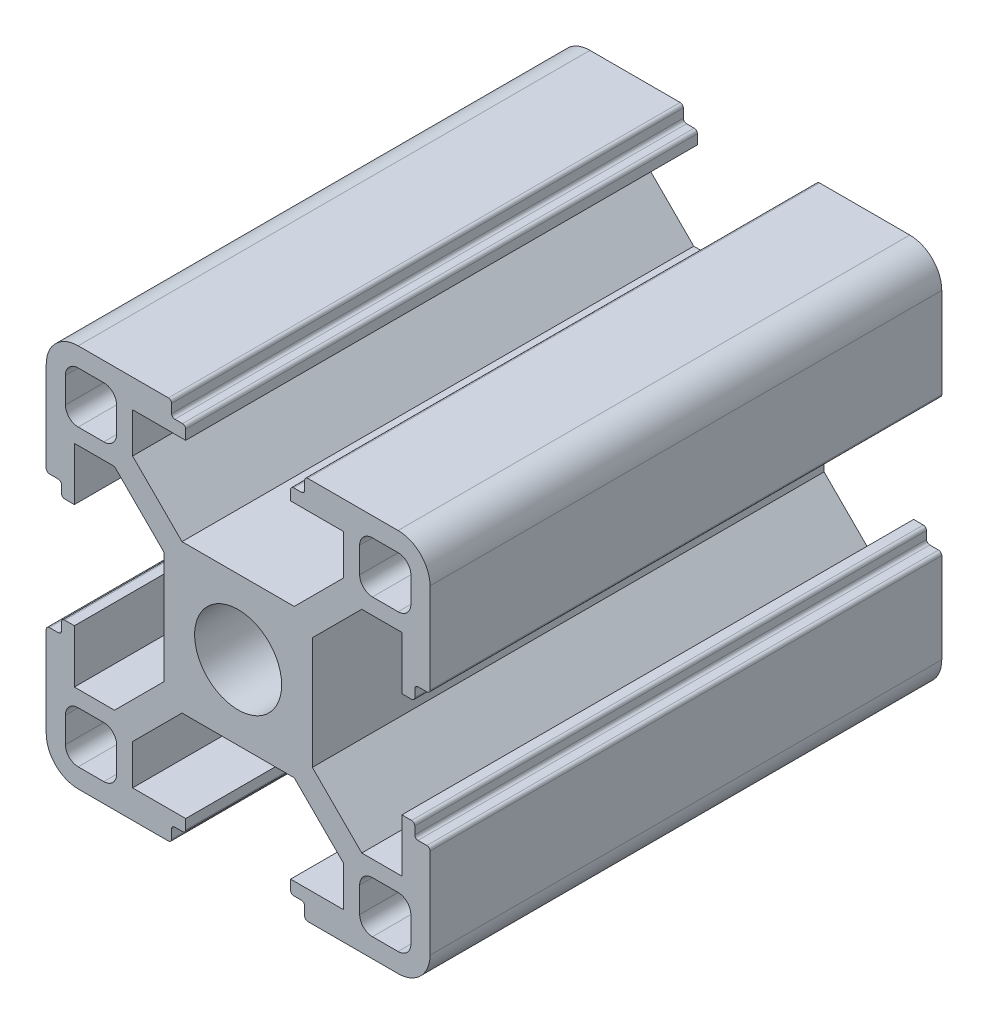
SolidWorks part; units mm, degrees
ref_plane "Front Plane" through (0, 0, 0) normal (0, 0, 1) x (1, 0, 0)
ref_plane "Top Plane" through (0, 0, 0) normal (0, 1, 0) x (1, 0, 0)
ref_plane "Right Plane" through (0, 0, 0) normal (1, 0, 0) x (0, 0, -1)
sketch "Sketch1" plane through (0, 0, 0) normal (0, 0, 1) x (1, 0, 0)
  line L0 (0, -5.8) -> (0, 5.8) construction
  line L1 (0, 0) -> (-15, 15) construction
  line L2 (-15, 15) -> (-5.2, 15)
  line L3 (-5.2, 15) -> (-5.2, 13.8083)
  line L4 (-5.2, 13.8083) -> (-4.1, 13.8083)
  line L5 (-4.1, 13.8083) -> (-4.1, 12.8)
  line L6 (-4.1, 12.8) -> (-8.25, 12.8)
  line L7 (-8.25, 12.8) -> (-8.25, 9.6642)
  line L8 (-8.25, 9.6642) -> (-4.3858, 5.8)
  line L9 (-4.3858, 5.8) -> (4.3858, 5.8)
  line L10 (-5.8, 4.3858) -> (-5.8, -4.3858)
  line L11 (-9.6642, 8.25) -> (-5.8, 4.3858)
  line L12 (-12.8, 8.25) -> (-9.6642, 8.25)
  line L13 (-12.8, 4.1) -> (-12.8, 8.25)
  line L14 (-13.8083, 4.1) -> (-12.8, 4.1)
  line L15 (-13.8083, 5.2) -> (-13.8083, 4.1)
  line L16 (-15, 5.2) -> (-13.8083, 5.2)
  line L17 (-15, 15) -> (-15, 5.2)
  line L18 (0, 0) -> (15, 15) construction
  line L19 (15, 15) -> (15, 5.2)
  line L20 (15, 5.2) -> (13.8083, 5.2)
  line L21 (13.8083, 5.2) -> (13.8083, 4.1)
  line L22 (13.8083, 4.1) -> (12.8, 4.1)
  line L23 (12.8, 4.1) -> (12.8, 8.25)
  line L24 (12.8, 8.25) -> (9.6642, 8.25)
  line L25 (9.6642, 8.25) -> (5.8, 4.3858)
  line L26 (5.8, 4.3858) -> (5.8, -4.3858)
  line L27 (8.25, 9.6642) -> (4.3858, 5.8)
  line L28 (8.25, 12.8) -> (8.25, 9.6642)
  line L29 (4.1, 12.8) -> (8.25, 12.8)
  line L30 (4.1, 13.8083) -> (4.1, 12.8)
  line L31 (5.2, 13.8083) -> (4.1, 13.8083)
  line L32 (5.2, 15) -> (5.2, 13.8083)
  line L33 (15, 15) -> (5.2, 15)
  line L34 (0, 0) -> (3.5826, 0) construction
  line L35 (0, 0) -> (15, -15) construction
  line L36 (0, 0) -> (-15, -15) construction
  line L37 (15, -15) -> (5.2, -15)
  line L38 (5.2, -15) -> (5.2, -13.8083)
  line L39 (5.2, -13.8083) -> (4.1, -13.8083)
  line L40 (4.1, -13.8083) -> (4.1, -12.8)
  line L41 (4.1, -12.8) -> (8.25, -12.8)
  line L42 (8.25, -12.8) -> (8.25, -9.6642)
  line L43 (8.25, -9.6642) -> (4.3858, -5.8)
  line L44 (9.6642, -8.25) -> (5.8, -4.3858)
  line L45 (12.8, -8.25) -> (9.6642, -8.25)
  line L46 (12.8, -4.1) -> (12.8, -8.25)
  line L47 (13.8083, -4.1) -> (12.8, -4.1)
  line L48 (13.8083, -5.2) -> (13.8083, -4.1)
  line L49 (15, -5.2) -> (13.8083, -5.2)
  line L50 (15, -15) -> (15, -5.2)
  line L51 (-15, -15) -> (-15, -5.2)
  line L52 (-15, -5.2) -> (-13.8083, -5.2)
  line L53 (-13.8083, -5.2) -> (-13.8083, -4.1)
  line L54 (-13.8083, -4.1) -> (-12.8, -4.1)
  line L55 (-12.8, -4.1) -> (-12.8, -8.25)
  line L56 (-12.8, -8.25) -> (-9.6642, -8.25)
  line L57 (-9.6642, -8.25) -> (-5.8, -4.3858)
  line L58 (-4.3858, -5.8) -> (4.3858, -5.8)
  line L59 (-8.25, -9.6642) -> (-4.3858, -5.8)
  line L60 (-8.25, -12.8) -> (-8.25, -9.6642)
  line L61 (-4.1, -12.8) -> (-8.25, -12.8)
  line L62 (-4.1, -13.8083) -> (-4.1, -12.8)
  line L63 (-5.2, -13.8083) -> (-4.1, -13.8083)
  line L64 (-5.2, -15) -> (-5.2, -13.8083)
  line L65 (-15, -15) -> (-5.2, -15)
  point P30 (0, 5.8)
  point P48 (5.8, 0)
  point P61 (-5.8, 0)
  dimension "D2" = 15
  dimension "D3" = 1
  dimension "D4" = 4.1
  dimension "D5" = 5.2
  dimension "D6" = 2.2
  dimension "D7" = 8.25
  dimension "D8" = 9.2
extrude "Boss-Extrude1" add sketch "Sketch1" along normal blind 250
sketch "Sketch2" plane through (0, 0, 250) normal (0, 0, 1) x (1, 0, 0)
  line L0 (0, 0) -> (0, 17.0054) construction
  line L1 (0, 0) -> (20.7717, 0) construction
  line L2 (-5.2, 15) -> (-15, 15) construction
  line L3 (-12.5, 13.5) -> (-10.5, 13.5)
  line L4 (-13.5, 12.5) -> (-13.5, 10.5)
  line L5 (-12.5, 9.5) -> (-10.5, 9.5)
  line L6 (-9.5, 12.5) -> (-9.5, 10.5)
  line L7 (-13.5, 13.5) -> (-9.5, 9.5) construction
  line L8 (-13.5, 9.5) -> (-9.5, 13.5) construction
  line L9 (-15, 15) -> (-15, 5.2) construction
  line L10 (13.5, 9.5) -> (9.5, 13.5) construction
  line L11 (13.5, 13.5) -> (9.5, 9.5) construction
  line L12 (9.5, 12.5) -> (9.5, 10.5)
  line L13 (12.5, 9.5) -> (10.5, 9.5)
  line L14 (13.5, 12.5) -> (13.5, 10.5)
  line L15 (12.5, 13.5) -> (10.5, 13.5)
  line L16 (13.5, -13.5) -> (9.5, -9.5) construction
  line L17 (13.5, -9.5) -> (9.5, -13.5) construction
  line L18 (-13.5, -9.5) -> (-9.5, -13.5) construction
  line L19 (-13.5, -13.5) -> (-9.5, -9.5) construction
  line L20 (12.5, -13.5) -> (10.5, -13.5)
  line L21 (13.5, -12.5) -> (13.5, -10.5)
  line L22 (12.5, -9.5) -> (10.5, -9.5)
  line L23 (9.5, -12.5) -> (9.5, -10.5)
  line L24 (-9.5, -12.5) -> (-9.5, -10.5)
  line L25 (-12.5, -9.5) -> (-10.5, -9.5)
  line L26 (-13.5, -12.5) -> (-13.5, -10.5)
  line L27 (-12.5, -13.5) -> (-10.5, -13.5)
  arc A0 (-12.5, 13.5) -> (-13.5, 12.5) centre (-12.5, 12.5) ccw
  arc A1 (-13.5, 10.5) -> (-12.5, 9.5) centre (-12.5, 10.5) ccw
  arc A2 (-10.5, 9.5) -> (-9.5, 10.5) centre (-10.5, 10.5) ccw
  arc A3 (-10.5, 13.5) -> (-9.5, 12.5) centre (-10.5, 12.5) cw
  arc A4 (10.5, 13.5) -> (9.5, 12.5) centre (10.5, 12.5) ccw
  arc A5 (10.5, 9.5) -> (9.5, 10.5) centre (10.5, 10.5) cw
  arc A6 (13.5, 10.5) -> (12.5, 9.5) centre (12.5, 10.5) cw
  arc A7 (12.5, 13.5) -> (13.5, 12.5) centre (12.5, 12.5) cw
  arc A8 (12.5, -13.5) -> (13.5, -12.5) centre (12.5, -12.5) ccw
  arc A9 (13.5, -10.5) -> (12.5, -9.5) centre (12.5, -10.5) ccw
  arc A10 (10.5, -9.5) -> (9.5, -10.5) centre (10.5, -10.5) ccw
  arc A11 (10.5, -13.5) -> (9.5, -12.5) centre (10.5, -12.5) cw
  arc A12 (-10.5, -13.5) -> (-9.5, -12.5) centre (-10.5, -12.5) ccw
  arc A13 (-10.5, -9.5) -> (-9.5, -10.5) centre (-10.5, -10.5) cw
  arc A14 (-13.5, -10.5) -> (-12.5, -9.5) centre (-12.5, -10.5) cw
  arc A15 (-12.5, -13.5) -> (-13.5, -12.5) centre (-12.5, -12.5) cw
  circle A16 centre (0, 0) radius 3.4
  point P3 (-11.5, 11.5)
  point P41 (11.5, 11.5)
  point P74 (11.5, -11.5)
  point P75 (-11.5, -11.5)
  dimension "D5" = 1
  dimension "D6" = 6.8
  dimension "D1" = 1.5
  dimension "D2" = 1.5
  dimension "D3" = 4
  dimension "D4" = 4
extrude "Cut-Extrude1" cut sketch "Sketch2" against normal through all
fillet "Fillet1" radius 2.5 4 edges at (-15, -15, 125) (15, -15, 125) (15, 15, 125) (-15, 15, 125)
fillet "Fillet2" radius 0.25 24 edges at (-13.8083, 5.2, 125) (-13.8083, 4.1, 125) (-15, 5.2, 125) (-13.8083, -4.1, 125) (-13.8083, -5.2, 125) (-15, -5.2, 125) (-5.2, -15, 125) (-5.2, -13.8083, 125) (-4.1, -13.8083, 125) (4.1, -13.8083, 125) (5.2, -13.8083, 125) (5.2, -15, 125) (13.8083, -5.2, 125) (13.8083, -4.1, 125) (15, -5.2, 125) (13.8083, 4.1, 125) (13.8083, 5.2, 125) (15, 5.2, 125) (-4.1, 13.8083, 125) (-5.2, 13.8083, 125) (4.1, 13.8083, 125) (5.2, 13.8083, 125) (5.2, 15, 125) (-5.2, 15, 125)
sketch "Sketch3" plane through (0, 0, 0) normal (0, 0, -1) x (-1, 0, 0)
  line L0 (-12.5, 13.5) -> (-10.5, 13.5) construction
  line L1 (-10.5, 9.5) -> (-12.5, 9.5) construction
  line L2 (-9.5, 12.5) -> (-9.5, 10.5) construction
  line L3 (-13.5, 10.5) -> (-13.5, 12.5) construction
  line L4 (-9.5, 12.5) -> (-9.5, 10.5)
  line L5 (-12.5, 13.5) -> (-10.5, 13.5)
  line L6 (-13.5, 10.5) -> (-13.5, 12.5)
  line L7 (-10.5, 9.5) -> (-12.5, 9.5)
  line L8 (10.5, 13.5) -> (12.5, 13.5) construction
  line L9 (9.5, 10.5) -> (9.5, 12.5) construction
  line L10 (13.5, 12.5) -> (13.5, 10.5) construction
  line L11 (12.5, 9.5) -> (10.5, 9.5) construction
  line L12 (12.5, 9.5) -> (10.5, 9.5)
  line L13 (13.5, 12.5) -> (13.5, 10.5)
  line L14 (9.5, 10.5) -> (9.5, 12.5)
  line L15 (10.5, 13.5) -> (12.5, 13.5)
  line L16 (9.5, -12.5) -> (9.5, -10.5) construction
  line L17 (12.5, -13.5) -> (10.5, -13.5) construction
  line L18 (13.5, -10.5) -> (13.5, -12.5) construction
  line L19 (10.5, -9.5) -> (12.5, -9.5) construction
  line L20 (9.5, -12.5) -> (9.5, -10.5)
  line L21 (12.5, -13.5) -> (10.5, -13.5)
  line L22 (13.5, -10.5) -> (13.5, -12.5)
  line L23 (10.5, -9.5) -> (12.5, -9.5)
  line L24 (-9.5, -10.5) -> (-9.5, -12.5) construction
  line L25 (-10.5, -13.5) -> (-12.5, -13.5) construction
  line L26 (-13.5, -12.5) -> (-13.5, -10.5) construction
  line L27 (-12.5, -9.5) -> (-10.5, -9.5) construction
  line L28 (-9.5, -10.5) -> (-9.5, -12.5)
  line L29 (-10.5, -13.5) -> (-12.5, -13.5)
  line L30 (-13.5, -12.5) -> (-13.5, -10.5)
  line L31 (-12.5, -9.5) -> (-10.5, -9.5)
  line L60 (12.8, 4.1) -> (13.5583, 4.1)
  line L61 (13.8083, 4.35) -> (13.8083, 4.95)
  line L62 (14.0583, 5.2) -> (14.75, 5.2)
  line L63 (15, 5.45) -> (15, 12.5)
  line L64 (12.5, 15) -> (5.45, 15)
  line L65 (5.2, 14.75) -> (5.2, 14.0583)
  line L66 (4.95, 13.8083) -> (4.35, 13.8083)
  line L67 (4.1, 13.5583) -> (4.1, 12.8)
  line L68 (4.1, 12.8) -> (8.25, 12.8)
  line L69 (8.25, 12.8) -> (8.25, 9.6642)
  line L70 (8.25, 9.6642) -> (4.3858, 5.8)
  line L71 (4.3858, 5.8) -> (-4.3858, 5.8)
  line L72 (-4.3858, 5.8) -> (-8.25, 9.6642)
  line L73 (-8.25, 9.6642) -> (-8.25, 12.8)
  line L74 (-8.25, 12.8) -> (-4.1, 12.8)
  line L75 (-4.1, 12.8) -> (-4.1, 13.5583)
  line L76 (-4.35, 13.8083) -> (-4.95, 13.8083)
  line L77 (-5.2, 14.0583) -> (-5.2, 14.75)
  line L78 (-5.45, 15) -> (-12.5, 15)
  line L79 (-15, 12.5) -> (-15, 5.45)
  line L80 (-14.75, 5.2) -> (-14.0583, 5.2)
  line L81 (-13.8083, 4.95) -> (-13.8083, 4.35)
  line L82 (-13.5583, 4.1) -> (-12.8, 4.1)
  line L83 (-12.8, 4.1) -> (-12.8, 8.25)
  line L84 (-12.8, 8.25) -> (-9.6642, 8.25)
  line L85 (-9.6642, 8.25) -> (-5.8, 4.3858)
  line L86 (-5.8, 4.3858) -> (-5.8, -4.3858)
  line L87 (-5.8, -4.3858) -> (-9.6642, -8.25)
  line L88 (-9.6642, -8.25) -> (-12.8, -8.25)
  line L89 (-12.8, -8.25) -> (-12.8, -4.1)
  line L90 (-12.8, -4.1) -> (-13.5583, -4.1)
  line L91 (-13.8083, -4.35) -> (-13.8083, -4.95)
  line L92 (-14.0583, -5.2) -> (-14.75, -5.2)
  line L93 (-15, -5.45) -> (-15, -12.5)
  line L94 (-12.5, -15) -> (-5.45, -15)
  line L95 (-5.2, -14.75) -> (-5.2, -14.0583)
  line L96 (-4.95, -13.8083) -> (-4.35, -13.8083)
  line L97 (-4.1, -13.5583) -> (-4.1, -12.8)
  line L98 (-4.1, -12.8) -> (-8.25, -12.8)
  line L99 (-8.25, -12.8) -> (-8.25, -9.6642)
  line L100 (-8.25, -9.6642) -> (-4.3858, -5.8)
  line L101 (-4.3858, -5.8) -> (4.3858, -5.8)
  line L102 (4.3858, -5.8) -> (8.25, -9.6642)
  line L103 (8.25, -9.6642) -> (8.25, -12.8)
  line L104 (8.25, -12.8) -> (4.1, -12.8)
  line L105 (4.1, -12.8) -> (4.1, -13.5583)
  line L106 (4.35, -13.8083) -> (4.95, -13.8083)
  line L107 (5.2, -14.0583) -> (5.2, -14.75)
  line L108 (5.45, -15) -> (12.5, -15)
  line L109 (15, -12.5) -> (15, -5.45)
  line L110 (14.75, -5.2) -> (14.0583, -5.2)
  line L111 (13.8083, -4.95) -> (13.8083, -4.35)
  line L112 (13.5583, -4.1) -> (12.8, -4.1)
  line L113 (12.8, -4.1) -> (12.8, -8.25)
  line L114 (12.8, -8.25) -> (9.6642, -8.25)
  line L115 (9.6642, -8.25) -> (5.8, -4.3858)
  line L116 (5.8, -4.3858) -> (5.8, 4.3858)
  line L117 (5.8, 4.3858) -> (9.6642, 8.25)
  line L118 (9.6642, 8.25) -> (12.8, 8.25)
  line L119 (12.8, 8.25) -> (12.8, 4.1)
  line L120 (12.8, 4.1) -> (13.5583, 4.1)
  line L121 (13.8083, 4.35) -> (13.8083, 4.95)
  line L122 (14.0583, 5.2) -> (14.75, 5.2)
  line L123 (15, 5.45) -> (15, 12.5)
  line L124 (12.5, 15) -> (5.45, 15)
  line L125 (5.2, 14.75) -> (5.2, 14.0583)
  line L126 (4.95, 13.8083) -> (4.35, 13.8083)
  line L127 (4.1, 13.5583) -> (4.1, 12.8)
  line L128 (4.1, 12.8) -> (8.25, 12.8)
  line L129 (8.25, 12.8) -> (8.25, 9.6642)
  line L130 (8.25, 9.6642) -> (4.3858, 5.8)
  line L131 (4.3858, 5.8) -> (-4.3858, 5.8)
  line L132 (-4.3858, 5.8) -> (-8.25, 9.6642)
  line L133 (-8.25, 9.6642) -> (-8.25, 12.8)
  line L134 (-8.25, 12.8) -> (-4.1, 12.8)
  line L135 (-4.1, 12.8) -> (-4.1, 13.5583)
  line L136 (-4.35, 13.8083) -> (-4.95, 13.8083)
  line L137 (-5.2, 14.0583) -> (-5.2, 14.75)
  line L138 (-5.45, 15) -> (-12.5, 15)
  line L139 (-15, 12.5) -> (-15, 5.45)
  line L140 (-14.75, 5.2) -> (-14.0583, 5.2)
  line L141 (-13.8083, 4.95) -> (-13.8083, 4.35)
  line L142 (-13.5583, 4.1) -> (-12.8, 4.1)
  line L143 (-12.8, 4.1) -> (-12.8, 8.25)
  line L144 (-12.8, 8.25) -> (-9.6642, 8.25)
  line L145 (-9.6642, 8.25) -> (-5.8, 4.3858)
  line L146 (-5.8, 4.3858) -> (-5.8, -4.3858)
  line L147 (-5.8, -4.3858) -> (-9.6642, -8.25)
  line L148 (-9.6642, -8.25) -> (-12.8, -8.25)
  line L149 (-12.8, -8.25) -> (-12.8, -4.1)
  line L150 (-12.8, -4.1) -> (-13.5583, -4.1)
  line L151 (-13.8083, -4.35) -> (-13.8083, -4.95)
  line L152 (-14.0583, -5.2) -> (-14.75, -5.2)
  line L153 (-15, -5.45) -> (-15, -12.5)
  line L154 (-12.5, -15) -> (-5.45, -15)
  line L155 (-5.2, -14.75) -> (-5.2, -14.0583)
  line L156 (-4.95, -13.8083) -> (-4.35, -13.8083)
  line L157 (-4.1, -13.5583) -> (-4.1, -12.8)
  line L158 (-4.1, -12.8) -> (-8.25, -12.8)
  line L159 (-8.25, -12.8) -> (-8.25, -9.6642)
  line L160 (-8.25, -9.6642) -> (-4.3858, -5.8)
  line L161 (-4.3858, -5.8) -> (4.3858, -5.8)
  line L162 (4.3858, -5.8) -> (8.25, -9.6642)
  line L163 (8.25, -9.6642) -> (8.25, -12.8)
  line L164 (8.25, -12.8) -> (4.1, -12.8)
  line L165 (4.1, -12.8) -> (4.1, -13.5583)
  line L166 (4.35, -13.8083) -> (4.95, -13.8083)
  line L167 (5.2, -14.0583) -> (5.2, -14.75)
  line L168 (5.45, -15) -> (12.5, -15)
  line L169 (15, -12.5) -> (15, -5.45)
  line L170 (14.75, -5.2) -> (14.0583, -5.2)
  line L171 (13.8083, -4.95) -> (13.8083, -4.35)
  line L172 (13.5583, -4.1) -> (12.8, -4.1)
  line L173 (12.8, -4.1) -> (12.8, -8.25)
  line L174 (12.8, -8.25) -> (9.6642, -8.25)
  line L175 (9.6642, -8.25) -> (5.8, -4.3858)
  line L176 (5.8, -4.3858) -> (5.8, 4.3858)
  line L177 (5.8, 4.3858) -> (9.6642, 8.25)
  line L178 (9.6642, 8.25) -> (12.8, 8.25)
  line L179 (12.8, 8.25) -> (12.8, 4.1)
  circle A0 centre (0, 0) radius 3.4 construction
  circle A1 centre (0, 0) radius 3.4
  arc A2 (-12.5, 13.5) -> (-13.5, 12.5) centre (-12.5, 12.5) ccw construction
  arc A3 (-9.5, 12.5) -> (-10.5, 13.5) centre (-10.5, 12.5) ccw construction
  arc A4 (-13.5, 10.5) -> (-12.5, 9.5) centre (-12.5, 10.5) ccw construction
  arc A5 (-10.5, 9.5) -> (-9.5, 10.5) centre (-10.5, 10.5) ccw construction
  arc A6 (-9.5, 12.5) -> (-10.5, 13.5) centre (-10.5, 12.5) ccw
  arc A7 (-12.5, 13.5) -> (-13.5, 12.5) centre (-12.5, 12.5) ccw
  arc A8 (-13.5, 10.5) -> (-12.5, 9.5) centre (-12.5, 10.5) ccw
  arc A9 (-10.5, 9.5) -> (-9.5, 10.5) centre (-10.5, 10.5) ccw
  arc A10 (13.5, 12.5) -> (12.5, 13.5) centre (12.5, 12.5) ccw construction
  arc A11 (10.5, 13.5) -> (9.5, 12.5) centre (10.5, 12.5) ccw construction
  arc A12 (12.5, 9.5) -> (13.5, 10.5) centre (12.5, 10.5) ccw construction
  arc A13 (9.5, 10.5) -> (10.5, 9.5) centre (10.5, 10.5) ccw construction
  arc A14 (9.5, 10.5) -> (10.5, 9.5) centre (10.5, 10.5) ccw
  arc A15 (12.5, 9.5) -> (13.5, 10.5) centre (12.5, 10.5) ccw
  arc A16 (10.5, 13.5) -> (9.5, 12.5) centre (10.5, 12.5) ccw
  arc A17 (13.5, 12.5) -> (12.5, 13.5) centre (12.5, 12.5) ccw
  arc A18 (10.5, -9.5) -> (9.5, -10.5) centre (10.5, -10.5) ccw construction
  arc A19 (9.5, -12.5) -> (10.5, -13.5) centre (10.5, -12.5) ccw construction
  arc A20 (12.5, -13.5) -> (13.5, -12.5) centre (12.5, -12.5) ccw construction
  arc A21 (13.5, -10.5) -> (12.5, -9.5) centre (12.5, -10.5) ccw construction
  arc A22 (10.5, -9.5) -> (9.5, -10.5) centre (10.5, -10.5) ccw
  arc A23 (9.5, -12.5) -> (10.5, -13.5) centre (10.5, -12.5) ccw
  arc A24 (12.5, -13.5) -> (13.5, -12.5) centre (12.5, -12.5) ccw
  arc A25 (13.5, -10.5) -> (12.5, -9.5) centre (12.5, -10.5) ccw
  arc A26 (-9.5, -10.5) -> (-10.5, -9.5) centre (-10.5, -10.5) ccw construction
  arc A27 (-10.5, -13.5) -> (-9.5, -12.5) centre (-10.5, -12.5) ccw construction
  arc A28 (13.5583, 4.1) -> (13.8083, 4.35) centre (13.5583, 4.35) ccw
  arc A29 (14.0583, 5.2) -> (13.8083, 4.95) centre (14.0583, 4.95) ccw
  arc A30 (14.75, 5.2) -> (15, 5.45) centre (14.75, 5.45) ccw
  arc A31 (15, 12.5) -> (12.5, 15) centre (12.5, 12.5) ccw
  arc A32 (5.45, 15) -> (5.2, 14.75) centre (5.45, 14.75) ccw
  arc A33 (4.95, 13.8083) -> (5.2, 14.0583) centre (4.95, 14.0583) ccw
  arc A34 (4.35, 13.8083) -> (4.1, 13.5583) centre (4.35, 13.5583) ccw
  arc A35 (-4.1, 13.5583) -> (-4.35, 13.8083) centre (-4.35, 13.5583) ccw
  arc A36 (-5.2, 14.0583) -> (-4.95, 13.8083) centre (-4.95, 14.0583) ccw
  arc A37 (-5.2, 14.75) -> (-5.45, 15) centre (-5.45, 14.75) ccw
  arc A38 (-12.5, 15) -> (-15, 12.5) centre (-12.5, 12.5) ccw
  arc A39 (-15, 5.45) -> (-14.75, 5.2) centre (-14.75, 5.45) ccw
  arc A40 (-13.8083, 4.95) -> (-14.0583, 5.2) centre (-14.0583, 4.95) ccw
  arc A41 (-13.8083, 4.35) -> (-13.5583, 4.1) centre (-13.5583, 4.35) ccw
  arc A42 (-13.5583, -4.1) -> (-13.8083, -4.35) centre (-13.5583, -4.35) ccw
  arc A43 (-14.0583, -5.2) -> (-13.8083, -4.95) centre (-14.0583, -4.95) ccw
  arc A44 (-14.75, -5.2) -> (-15, -5.45) centre (-14.75, -5.45) ccw
  arc A45 (-15, -12.5) -> (-12.5, -15) centre (-12.5, -12.5) ccw
  arc A46 (-5.45, -15) -> (-5.2, -14.75) centre (-5.45, -14.75) ccw
  arc A47 (-4.95, -13.8083) -> (-5.2, -14.0583) centre (-4.95, -14.0583) ccw
  arc A48 (-4.35, -13.8083) -> (-4.1, -13.5583) centre (-4.35, -13.5583) ccw
  arc A49 (4.1, -13.5583) -> (4.35, -13.8083) centre (4.35, -13.5583) ccw
  arc A50 (5.2, -14.0583) -> (4.95, -13.8083) centre (4.95, -14.0583) ccw
  arc A51 (5.2, -14.75) -> (5.45, -15) centre (5.45, -14.75) ccw
  arc A52 (12.5, -15) -> (15, -12.5) centre (12.5, -12.5) ccw
  arc A53 (15, -5.45) -> (14.75, -5.2) centre (14.75, -5.45) ccw
  arc A54 (13.8083, -4.95) -> (14.0583, -5.2) centre (14.0583, -4.95) ccw
  arc A55 (13.8083, -4.35) -> (13.5583, -4.1) centre (13.5583, -4.35) ccw
  arc A56 (13.5583, 4.1) -> (13.8083, 4.35) centre (13.5583, 4.35) ccw
  arc A57 (14.0583, 5.2) -> (13.8083, 4.95) centre (14.0583, 4.95) ccw
  arc A58 (14.75, 5.2) -> (15, 5.45) centre (14.75, 5.45) ccw
  arc A59 (15, 12.5) -> (12.5, 15) centre (12.5, 12.5) ccw
  arc A60 (5.45, 15) -> (5.2, 14.75) centre (5.45, 14.75) ccw
  arc A61 (4.95, 13.8083) -> (5.2, 14.0583) centre (4.95, 14.0583) ccw
  arc A62 (4.35, 13.8083) -> (4.1, 13.5583) centre (4.35, 13.5583) ccw
  arc A63 (-4.1, 13.5583) -> (-4.35, 13.8083) centre (-4.35, 13.5583) ccw
  arc A64 (-5.2, 14.0583) -> (-4.95, 13.8083) centre (-4.95, 14.0583) ccw
  arc A65 (-5.2, 14.75) -> (-5.45, 15) centre (-5.45, 14.75) ccw
  arc A66 (-12.5, 15) -> (-15, 12.5) centre (-12.5, 12.5) ccw
  arc A67 (-15, 5.45) -> (-14.75, 5.2) centre (-14.75, 5.45) ccw
  arc A68 (-13.8083, 4.95) -> (-14.0583, 5.2) centre (-14.0583, 4.95) ccw
  arc A69 (-13.8083, 4.35) -> (-13.5583, 4.1) centre (-13.5583, 4.35) ccw
  arc A70 (-13.5583, -4.1) -> (-13.8083, -4.35) centre (-13.5583, -4.35) ccw
  arc A71 (-14.0583, -5.2) -> (-13.8083, -4.95) centre (-14.0583, -4.95) ccw
  arc A72 (-14.75, -5.2) -> (-15, -5.45) centre (-14.75, -5.45) ccw
  arc A73 (-15, -12.5) -> (-12.5, -15) centre (-12.5, -12.5) ccw
  arc A74 (-5.45, -15) -> (-5.2, -14.75) centre (-5.45, -14.75) ccw
  arc A75 (-4.95, -13.8083) -> (-5.2, -14.0583) centre (-4.95, -14.0583) ccw
  arc A76 (-4.35, -13.8083) -> (-4.1, -13.5583) centre (-4.35, -13.5583) ccw
  arc A77 (4.1, -13.5583) -> (4.35, -13.8083) centre (4.35, -13.5583) ccw
  arc A78 (5.2, -14.0583) -> (4.95, -13.8083) centre (4.95, -14.0583) ccw
  arc A79 (5.2, -14.75) -> (5.45, -15) centre (5.45, -14.75) ccw
  arc A80 (12.5, -15) -> (15, -12.5) centre (12.5, -12.5) ccw
  arc A81 (15, -5.45) -> (14.75, -5.2) centre (14.75, -5.45) ccw
  arc A82 (13.8083, -4.95) -> (14.0583, -5.2) centre (14.0583, -4.95) ccw
  arc A83 (13.8083, -4.35) -> (13.5583, -4.1) centre (13.5583, -4.35) ccw
  arc A84 (-13.5, -12.5) -> (-12.5, -13.5) centre (-12.5, -12.5) ccw construction
  arc A85 (-12.5, -9.5) -> (-13.5, -10.5) centre (-12.5, -10.5) ccw construction
  arc A86 (-9.5, -10.5) -> (-10.5, -9.5) centre (-10.5, -10.5) ccw
  arc A87 (-10.5, -13.5) -> (-9.5, -12.5) centre (-10.5, -12.5) ccw
  arc A88 (-13.5, -12.5) -> (-12.5, -13.5) centre (-12.5, -12.5) ccw
  arc A89 (-12.5, -9.5) -> (-13.5, -10.5) centre (-12.5, -10.5) ccw
  dimension "D1" = 0
extrude "Cut-Extrude3" cut sketch "Sketch3" against normal blind 210
